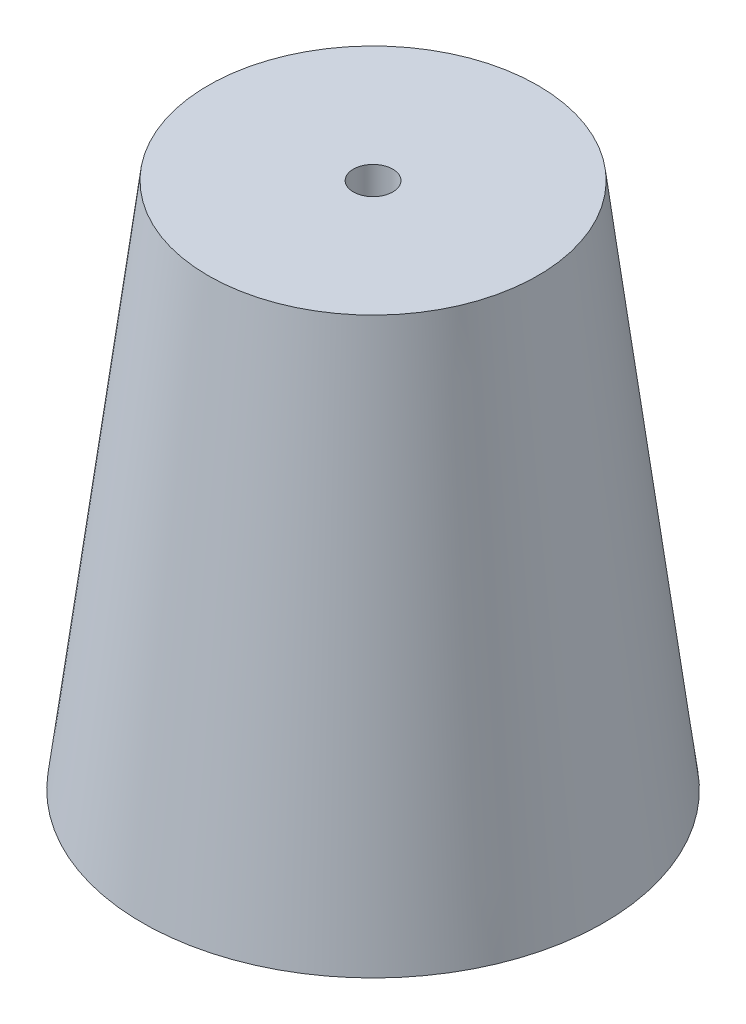
SolidWorks part; units mm, degrees
ref_plane "Alzado" through (0, 0, 0) normal (0, 0, 1) x (1, 0, 0)
ref_plane "Planta" through (0, 0, 0) normal (0, 1, 0) x (1, 0, 0)
ref_plane "Vista lateral" through (0, 0, 0) normal (1, 0, 0) x (0, 0, -1)
sketch "Croquis2" plane through (0, 0, 0) normal (1, 0, 0) x (0, 0, -1)
  line L0 (0, 0) -> (25, 0)
  line L1 (25, 0) -> (35, -80)
  line L2 (35, -80) -> (20, -80)
  line L3 (20, -80) -> (11.25, -10)
  line L4 (11.25, -10) -> (0, -10)
  line L5 (0, -10) -> (0, 0)
  dimension "D1" = 25
  dimension "D2" = 35
  dimension "D3" = 15
  dimension "D4" = 80
  dimension "D5" = 10
revolve "Revolución1" add sketch "Croquis2" angle 360 about L5
sketch "Croquis5" plane through (0, 0, 0) normal (1, 0, 0) x (0, 0, -1)
  line L0 (0, -10) -> (0, 0)
  line L1 (-11.25, -10) -> (11.25, -10) construction
  line L2 (0, 0) -> (2.9975, 0)
  line L3 (25, 0) -> (-25, 0) construction
  line L4 (2.9975, 0) -> (2.9975, -5)
  line L5 (2.9975, -5) -> (6, -10)
  line L6 (6, -10) -> (0, -10)
  dimension "D1" = 6
  dimension "D2" = 5
  dimension "D3" = 2.9975
revolve "Cortar-Revolución1" cut sketch "Croquis5" angle 360 about L0
